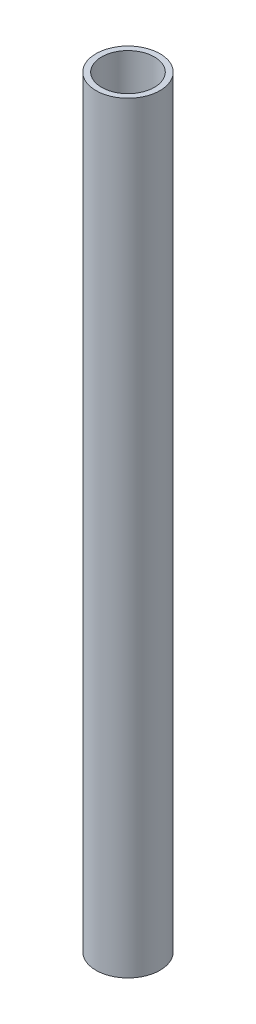
SolidWorks part; units mm, degrees
ref_plane "정면" through (0, 0, 0) normal (0, 0, 1) x (1, 0, 0)
ref_plane "윗면" through (0, 0, 0) normal (0, 1, 0) x (1, 0, 0)
ref_plane "우측면" through (0, 0, 0) normal (1, 0, 0) x (0, 0, -1)
sketch "스케치1" plane through (0, 0, 0) normal (0, 1, 0) x (1, 0, 0)
  circle A0 centre (0, 0) radius 12.6
  dimension "D1" = 25.2
extrude "보스-돌출1" add sketch "스케치1" along normal blind 300
shell "쉘1" thickness 2.2
